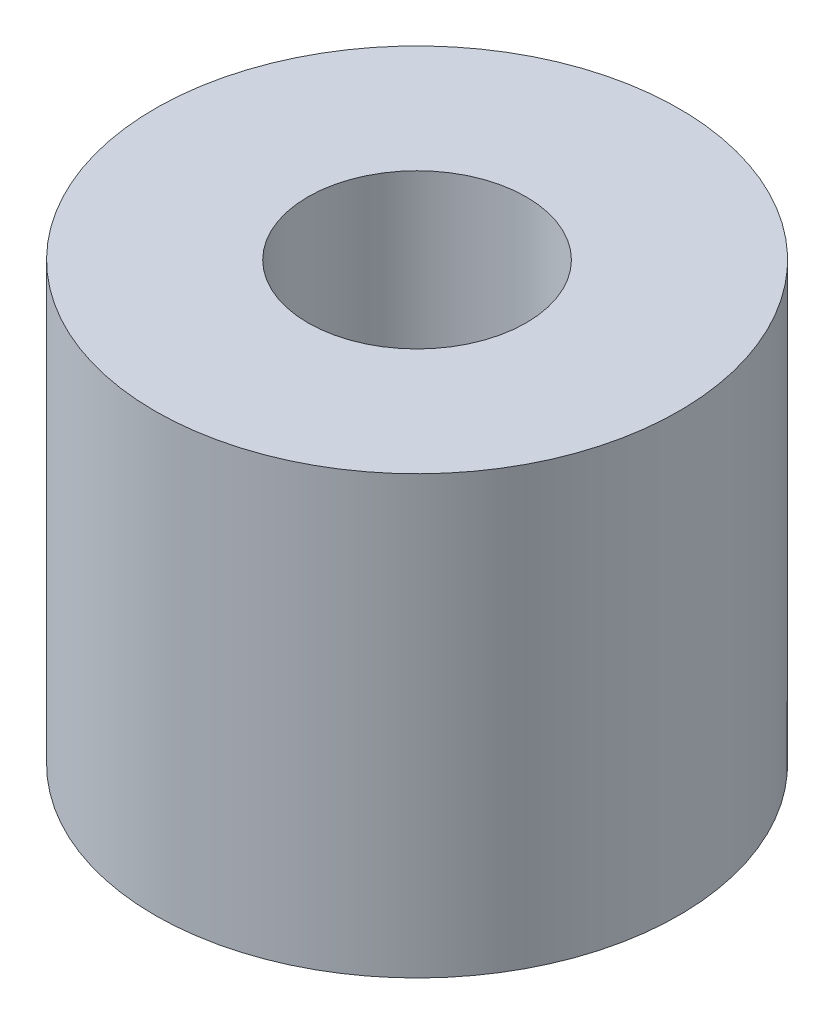
SolidWorks part; units mm, degrees
ref_plane "Спереди" through (0, 0, 0) normal (0, 0, 1) x (1, 0, 0)
ref_plane "Сверху" through (0, 0, 0) normal (0, 1, 0) x (1, 0, 0)
ref_plane "Справа" through (0, 0, 0) normal (1, 0, 0) x (0, 0, -1)
sketch "Эскиз1" plane through (0, 0, 0) normal (0, 1, 0) x (1, 0, 0)
  circle A0 centre (0, 0) radius 1.25
  circle A1 centre (0, 0) radius 3
  dimension "D1" = 6
  dimension "D2" = 2.5
extrude "Бобышка-Вытянуть1" add sketch "Эскиз1" along normal blind 5
